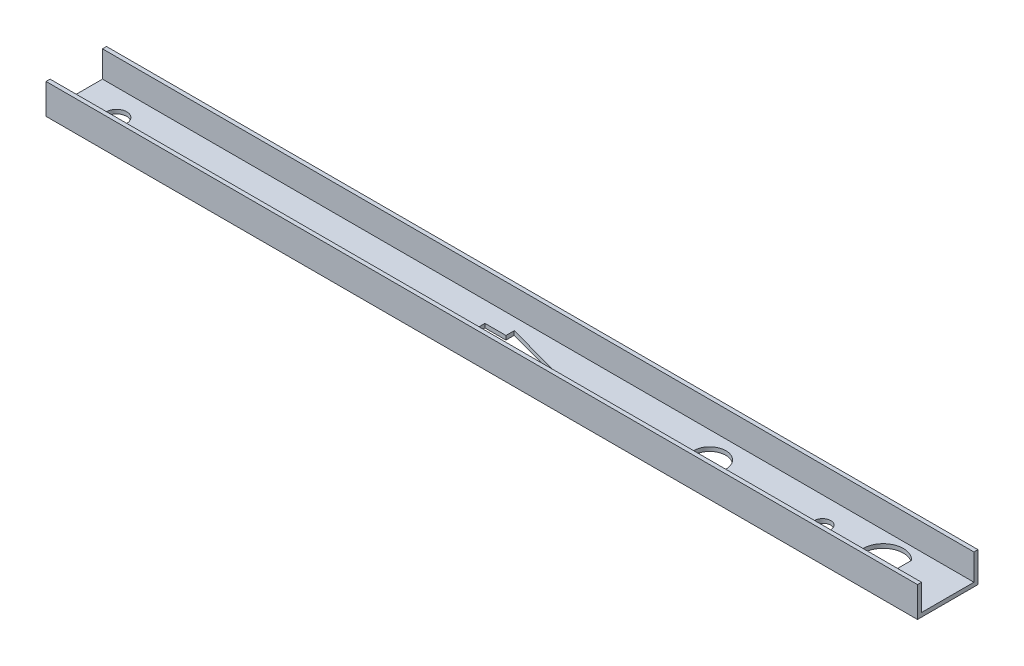
SolidWorks part; units mm, degrees
ref_plane "Plan de face" through (0, 0, 0) normal (0, 0, 1) x (1, 0, 0)
ref_plane "Plan de dessus" through (0, 0, 0) normal (0, 1, 0) x (1, 0, 0)
ref_plane "Plan de droite" through (0, 0, 0) normal (1, 0, 0) x (0, 0, -1)
sketch "Esquisse1" plane through (0, 0, 0) normal (1, 0, 0) x (0, 0, -1)
  line L0 (-7.5, 6.5) -> (-7.5, -1)
  line L1 (-7.5, -1) -> (7.5, -1)
  line L5 (6.5, 0) -> (-6.5, 0)
  line L6 (-6.5, 0) -> (-6.5, 6.5)
  line L7 (-6.5, 6.5) -> (-7.5, 6.5)
  line L8 (0, 12.5915) -> (0, -18.4451) construction
  line L9 (6.5, 6.5) -> (7.5, 6.5)
  line L10 (7.5, 6.5) -> (7.5, -1)
  line L11 (6.5, 0) -> (6.5, 6.5)
  dimension "D1" = 15
  dimension "D2" = 1
  dimension "D3" = 1
  dimension "D4" = 7.5
extrude "Boss.-Extru.1" add sketch "Esquisse1" along normal mid plane 216
sketch "Esquisse2" plane through (0, 0, 0) normal (0, 1, 0) x (1, 0, 0)
  line L0 (95.5707, 3.5) -> (95.5707, -3.5)
  line L1 (-8.1759, 1.4735) -> (-8.1759, -1.5013)
  line L2 (-8.1759, -1.5013) -> (-2.9701, -1.5013)
  line L3 (-2.9701, -1.5013) -> (-2.9701, -3.2675)
  line L4 (-2.9701, -3.2675) -> (10.1373, 0)
  line L5 (10.1373, 0) -> (-2.9701, 3.5186)
  line L6 (-2.9701, 3.5186) -> (-2.9701, 1.4735)
  line L7 (-2.9701, 1.4735) -> (-8.1759, 1.4735)
  line L8 (0, 0) -> (179.2469, 0) construction
  line L9 (-108, 6.5) -> (-108, -6.5) construction
  circle A0 centre (-98, 0) radius 2.5
  circle A1 centre (49, 0) radius 4
  circle A2 centre (77, 0) radius 2
  arc A3 (95.5707, 3.5) -> (95.5707, -3.5) centre (92, 0) ccw
  dimension "D2" = 5
  dimension "D4" = 8
  dimension "D5" = 4
  dimension "D6" = 5
  dimension "D1" = 10
  dimension "D3" = 157
  dimension "D7" = 7
  dimension "D8" = 185
  dimension "D9" = 200
extrude "Enlèv. mat.-Extru.1" cut sketch "Esquisse2" against normal through all
